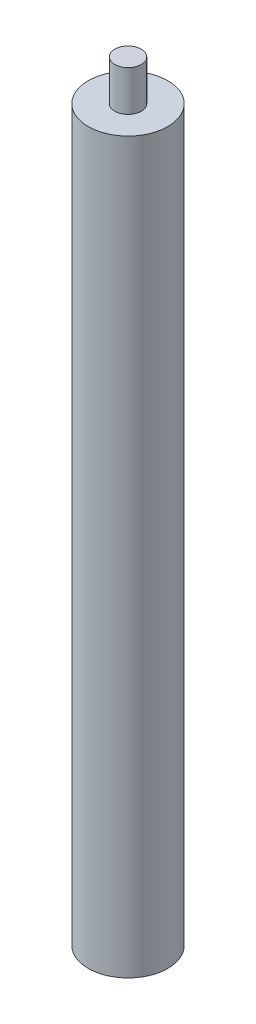
SolidWorks part; units mm, degrees
ref_plane "Plan de face" through (0, 0, 0) normal (0, 0, 1) x (1, 0, 0)
ref_plane "Plan de dessus" through (0, 0, 0) normal (0, 1, 0) x (1, 0, 0)
ref_plane "Plan de droite" through (0, 0, 0) normal (1, 0, 0) x (0, 0, -1)
sketch "Esquisse1" plane through (0, 0, 0) normal (0, 0, 1) x (1, 0, 0)
  line L0 (0, 0) -> (0, 21.0556) construction
  line L1 (3, 54.0556) -> (1, 54.0556)
  line L2 (3, 54.0556) -> (3, -0.9444)
  line L3 (3, -0.9444) -> (0, -0.9444)
  line L4 (0, -0.9444) -> (0, 9.0556)
  line L7 (1, 54.0556) -> (1, 57.1127)
  line L8 (1, 57.1127) -> (0, 57.1127)
  line L9 (0, 57.1127) -> (0, 9.0556)
  point P5 (1, 55.5841)
  dimension "D1" = 3
  dimension "D2" = 1
  dimension "D3" = 55
  dimension "D4" = 3.0571
revolve "Révolution1" add sketch "Esquisse1" angle 360 about L0
